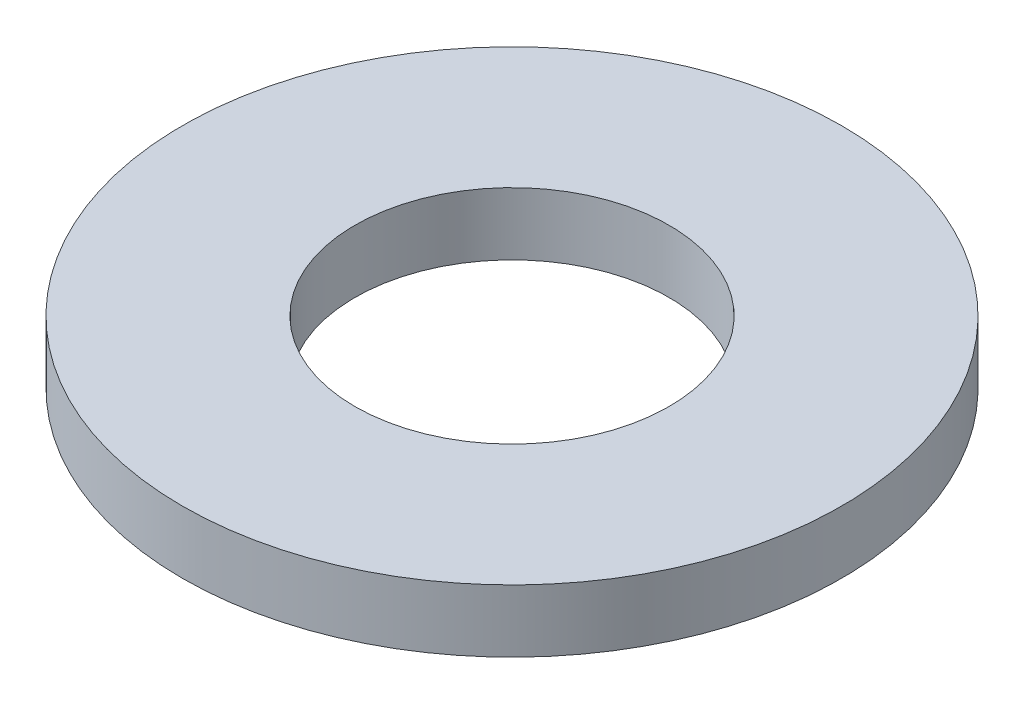
SolidWorks part; units mm, degrees
material "Copper"
ref_plane "Front Plane" through (0, 0, 0) normal (0, 0, 1) x (1, 0, 0)
ref_plane "Top Plane" through (0, 0, 0) normal (0, 1, 0) x (1, 0, 0)
ref_plane "Right Plane" through (0, 0, 0) normal (1, 0, 0) x (0, 0, -1)
sketch "Sketch1" plane through (0, 0, 0) normal (0, 1, 0) x (1, 0, 0)
  circle A0 centre (0, 0) radius 2.55
  circle A1 centre (0, 0) radius 5.35
  dimension "D1" = 2.8
  dimension "D2" = 5.1
extrude "Boss-Extrude1" add sketch "Sketch1" along normal blind 1.016
